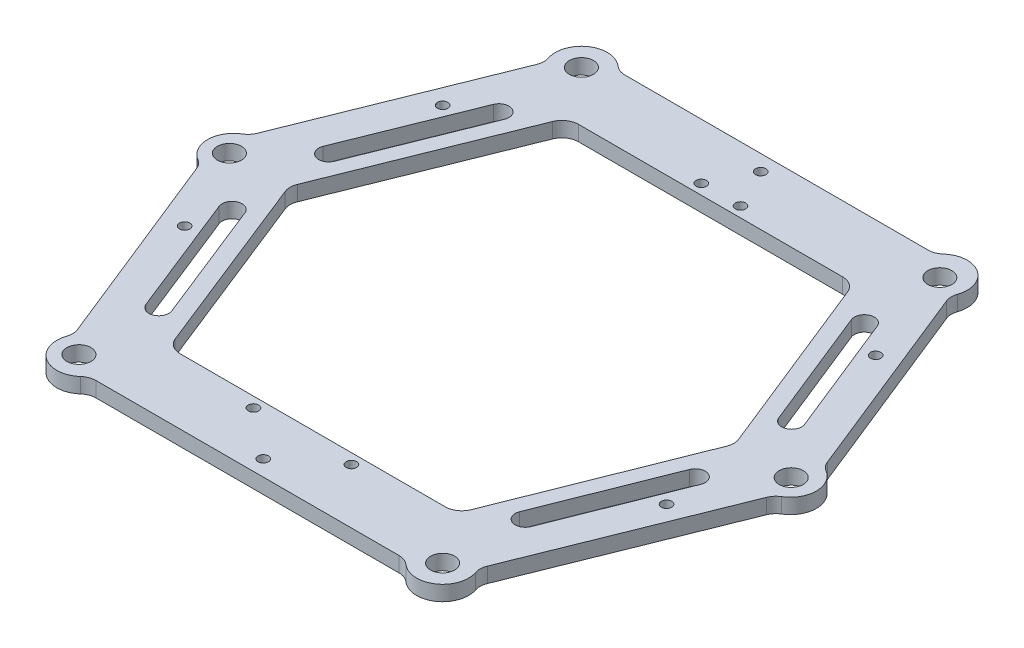
SolidWorks part; units mm, degrees
ref_plane "Front Plane" through (0, 0, 0) normal (0, 0, 1) x (1, 0, 0)
ref_plane "Top Plane" through (0, 0, 0) normal (0, 1, 0) x (1, 0, 0)
ref_plane "Right Plane" through (0, 0, 0) normal (1, 0, 0) x (0, 0, -1)
sketch "Sketch1" plane through (0, 0, 0) normal (0, 1, 0) x (1, 0, 0)
  line L0 (0, 0) -> (0, 80.8355) construction
  line L1 (0, 0) -> (0, -80.8355) construction
  line L2 (0, 0) -> (0, 60.6933) construction
  line L3 (0, 0) -> (0, -60.6933) construction
  line L4 (0, 0) -> (85.09, 0) construction
  line L5 (0, 0) -> (-85.09, 0) construction
  line L6 (0, 0) -> (-54.991, 76.2) construction
  line L7 (0, 0) -> (54.991, -76.2) construction
  line L8 (0, 0) -> (54.991, 76.2) construction
  line L9 (0, 0) -> (-54.991, -76.2) construction
  line L10 (-54.991, 0) -> (-54.991, 76.2) construction
  line L11 (-54.991, 0) -> (-54.991, -76.2) construction
  line L12 (0, 80.8355) -> (58.3363, 80.8355)
  line L13 (0, 80.8355) -> (-58.3363, 80.8355)
  line L14 (58.3363, 80.8355) -> (54.991, 76.2) construction
  line L15 (85.09, 0) -> (90.8065, 0) construction
  line L16 (58.3363, 80.8355) -> (90.8065, 0)
  line L17 (0, 60.6933) -> (43.8003, 60.6933)
  line L19 (54.991, -76.2) -> (58.3363, -80.8355) construction
  line L20 (-54.991, -76.2) -> (-58.3363, -80.8355) construction
  line L21 (-85.09, 0) -> (-90.8065, 0) construction
  line L22 (90.8065, 0) -> (58.3363, -80.8355)
  line L23 (58.3363, -80.8355) -> (-58.3363, -80.8355)
  line L24 (-58.3363, -80.8355) -> (-90.8065, 0)
  line L25 (-90.8065, 0) -> (-58.3363, 80.8355)
  line L26 (0, 60.6933) -> (-43.8003, 60.6933)
  line L29 (-43.947, -60.8965) -> (43.947, -60.8965)
  line L31 (43.8003, 60.6933) -> (68.1798, 0)
  line L32 (68.1798, 0) -> (43.947, -60.8965)
  line L33 (-43.8003, 60.6933) -> (-68.1798, 0)
  line L34 (-68.1798, 0) -> (-43.947, -60.8965)
  circle A0 centre (54.991, 76.2) radius 7.9375
  circle A1 centre (85.09, 0) radius 7.9375
  circle A2 centre (54.991, -76.2) radius 7.9375
  circle A3 centre (-54.991, -76.2) radius 7.9375
  circle A4 centre (-85.09, 0) radius 7.9375
  circle A5 centre (-54.991, 76.2) radius 7.9375
  point P31 (67.7678, 0)
  dimension "D6" = 15.875
  dimension "D1" = 161.671
  dimension "D2" = 20.1422
  dimension "D3" = 152.4
  dimension "D4" = 109.982
  dimension "D5" = 170.18
  dimension "D7" = 19.939
extrude "Boss-Extrude1" add sketch "Sketch1" along normal blind 4.6228 contours L25 L24 L23 L22 L16 L12 L13 L32 L29 L34 L33 L26 L17 L31 | L13 A5 L25 | L25 A5 L13 | L16 A0 L12 | L12 A0 L16 | L22 A1 L16 | L16 A1 L22 | L23 A2 L22 | L22 A2 L23 | L23 A3 L24 | L24 A3 L23 | L24 A4 L25 | L25 A4 L24
hole_wizard "L (0.29) Diameter Hole1" positions "Sketch2" profile "Sketch3" hole size "L" standard "ANSI Inch" end condition through all
sketch "Sketch2" plane through (0, 4.6228, 0) normal (0, 1, 0) x (1, 0, 0)
  point P0 (-54.991, 76.2)
  point P3 (85.6179, -0.2927)
  point P5 (55.3927, 75.3576)
  point P7 (54.991, -76.2)
  point P10 (-55.7883, -76.5703)
  point P12 (-86.0698, -0.2927)
  point P17 (0, 0)
sketch "Sketch3" plane through (-54.991, 4.6228, -76.2) normal (1, 0, 0) x (0, 0, 1)
  line L0 (0, 0) -> (0, 4.6228)
  line L1 (0, 4.6228) -> (3.683, 4.6228)
  line L2 (3.683, 4.6228) -> (3.683, 0)
  line L5 (3.683, 0) -> (0, 0)
  line L11 (0, -6.35) -> (0, 107.95) construction
  dimension "Thru Hole Dia." = 7.366
  dimension "Thru Hole Depth" = 4.6228
sketch "Sketch4" plane through (0, 0, 0) normal (0, 1, 0) x (1, 0, 0)
  line L0 (0, 0.9062) -> (0, -64.0461) construction
  line L1 (0, -64.0461) -> (14.9733, -64.0461) construction
  line L2 (0, -64.0461) -> (-14.9733, -64.0461) construction
  line L3 (0, 0.9062) -> (0, 63.8429) construction
  line L4 (0, 63.8429) -> (5.988, 63.8429) construction
  line L5 (0, 63.8429) -> (-5.988, 63.8429) construction
  line L6 (0, 63.8429) -> (0, 60.6933) construction
  line L7 (43.8003, 60.6933) -> (-43.8003, 60.6933) construction
  line L8 (0, -64.0461) -> (0, -60.8965) construction
  line L9 (-43.947, -60.8965) -> (43.947, -60.8965) construction
  line L10 (0, 0.9062) -> (0, 76.0095) construction
  line L11 (0, 0.9062) -> (0, -76.0095) construction
  line L12 (0, 76.0095) -> (0, 80.8355) construction
  line L13 (0, -76.0095) -> (0, -80.8355) construction
  line L14 (-48.5477, 80.8355) -> (48.5477, 80.8355) construction
  line L15 (48.5477, -80.8355) -> (-48.5477, -80.8355) construction
  line L16 (0, 44.9702) -> (66.1733, 44.9702) construction
  line L17 (0, 44.9702) -> (-66.1733, 44.9702) construction
  line L18 (0, -26.3953) -> (73.6346, -26.3953) construction
  line L19 (0, -26.3953) -> (-73.6346, -26.3953) construction
  line L20 (-66.1733, 44.9702) -> (-71.8301, 47.2424) construction
  line L21 (-87.8114, 7.4564) -> (-61.822, 72.1576) construction
  line L22 (-73.6346, -26.3953) -> (-79.2913, -28.6675) construction
  line L23 (-61.822, -72.1576) -> (-87.8114, -7.4564) construction
  point P33 (66.1733, -40.5517)
  point P35 (64.6197, -39.8714)
  point P36 (0, 0)
  point P37 (68.0505, -40.297)
  dimension "D1" = 29.9466
  dimension "D2" = 11.9761
  dimension "D3" = 127.889
  dimension "D4" = 152.019
  dimension "D5" = 132.3467
  dimension "D6" = 6.096
  dimension "D7" = 147.2692
hole_wizard "1/8 (0.125) Diameter Hole1" positions "3DSketch3" profile "Sketch6" hole size "1/8" standard "ANSI Inch" end condition through all
sketch3d "3DSketch3"
  point P0 (-73.6346, 0, 26.3953)
  point P3 (-66.1733, 0, -44.9702)
  point P6 (66.1733, 0, -44.9702)
  point P9 (73.6346, 0, 26.3953)
  point P12 (0, 0, 76.0095)
  point P15 (14.9733, 0, 64.0461)
  point P18 (-14.9733, 0, 64.0461)
  point P21 (5.988, 0, -63.8429)
  point P24 (-5.988, 0, -63.8429)
  point P27 (0, 0, -76.0095)
  point P31 (14.9733, 0, 64.0461)
  point P33 (14.9733, 0, 64.0461)
  point P35 (-14.9733, 0, 64.0461)
  point P37 (-14.9733, 0, 64.0461)
  point P39 (73.6346, 0, 26.3953)
  point P45 (0, 0, 76.0095)
  point P48 (0, 0, 76.0095)
  point P50 (-73.6346, 0, 26.3953)
  point P52 (-66.1733, 0, -44.9702)
  point P54 (66.1733, 0, -44.9702)
  point P56 (5.988, 0, -63.8429)
  point P58 (-5.988, 0, -63.8429)
  point P60 (0, 0, -76.0095)
  point P63 (0, 0, -76.0095)
  point P64 (-5.988, 0, -63.8429)
  point P65 (5.988, 0, -63.8429)
  point P66 (66.1733, 0, -44.9702)
  point P67 (-66.1733, 0, -44.9702)
  point P68 (-73.6346, 0, 26.3953)
  point P69 (0, 0, 76.0095)
sketch "Sketch6" plane through (0, 0, -76.0095) normal (1, 0, 0) x (0, 0, -1)
  line L0 (0, 0) -> (0, 4.6228)
  line L1 (0, 4.6228) -> (1.5875, 4.6228)
  line L2 (1.5875, 4.6228) -> (1.5875, 0)
  line L5 (1.5875, 0) -> (0, 0)
  line L11 (0, -6.35) -> (0, 107.95) construction
  dimension "Thru Hole Dia." = 3.175
  dimension "Thru Hole Depth" = 4.6228
sketch "Sketch7" plane through (0, 4.6228, 0) normal (0, 1, 0) x (1, 0, 0)
  line L0 (-56.0634, -30.4482) -> (-63.3794, -33.3595) construction
  line L1 (-68.1798, 0) -> (-43.947, -60.8965) construction
  line L2 (-63.3794, -33.3595) -> (-70.7751, -14.7745) construction
  line L3 (-63.3794, -33.3595) -> (-55.9838, -51.9446) construction
  line L4 (-70.7751, -14.7745) -> (-55.9838, -51.9446) construction
  line L5 (-67.943, -13.6475) -> (-53.1518, -50.8177)
  line L6 (-73.6071, -15.9014) -> (-58.8158, -53.0716)
  line L7 (-70.7751, -14.7745) -> (-71.902, -11.9425) construction
  line L8 (-55.9838, -51.9446) -> (-54.8568, -54.7766) construction
  line L9 (-55.9901, 30.3466) -> (-63.2966, 33.2816) construction
  line L10 (-43.8003, 60.6933) -> (-68.1798, 0) construction
  line L11 (-63.2966, 33.2816) -> (-55.841, 51.8426) construction
  line L12 (-55.841, 51.8426) -> (-54.7049, 54.671) construction
  line L13 (-63.2966, 33.2816) -> (-70.7523, 14.7205) construction
  line L14 (-70.7523, 14.7205) -> (-71.8884, 11.8922) construction
  line L15 (-55.841, 51.8426) -> (-70.7523, 14.7205) construction
  line L16 (-53.0126, 50.7065) -> (-67.924, 13.5844)
  line L17 (-58.6693, 52.9787) -> (-73.5807, 15.8566)
  line L18 (0, 0) -> (0, 76.0095) construction
  line L19 (70.7523, 14.7205) -> (71.8884, 11.8922) construction
  line L20 (63.2966, 33.2816) -> (70.7523, 14.7205) construction
  line L21 (55.841, 51.8426) -> (54.7049, 54.671) construction
  line L22 (63.2966, 33.2816) -> (55.841, 51.8426) construction
  line L23 (55.9901, 30.3466) -> (63.2966, 33.2816) construction
  line L24 (55.9838, -51.9446) -> (54.8568, -54.7766) construction
  line L25 (70.7751, -14.7745) -> (71.902, -11.9425) construction
  line L26 (63.3794, -33.3595) -> (55.9838, -51.9446) construction
  line L27 (63.3794, -33.3595) -> (70.7751, -14.7745) construction
  line L28 (56.0634, -30.4482) -> (63.3794, -33.3595) construction
  line L29 (55.841, 51.8426) -> (70.7523, 14.7205) construction
  line L30 (53.0126, 50.7065) -> (67.924, 13.5844)
  line L31 (58.6693, 52.9787) -> (73.5807, 15.8566)
  line L32 (70.7751, -14.7745) -> (55.9838, -51.9446) construction
  line L33 (67.943, -13.6475) -> (53.1518, -50.8177)
  line L34 (73.6071, -15.9014) -> (58.8158, -53.0716)
  arc A0 (-67.943, -13.6475) -> (-73.6071, -15.9014) centre (-70.7751, -14.7745) ccw
  arc A1 (-58.8158, -53.0716) -> (-53.1518, -50.8177) centre (-55.9838, -51.9446) ccw
  arc A2 (-53.0126, 50.7065) -> (-58.6693, 52.9787) centre (-55.841, 51.8426) ccw
  arc A3 (-73.5807, 15.8566) -> (-67.924, 13.5844) centre (-70.7523, 14.7205) ccw
  arc A4 (53.0126, 50.7065) -> (58.6693, 52.9787) centre (55.841, 51.8426) cw
  arc A5 (73.5807, 15.8566) -> (67.924, 13.5844) centre (70.7523, 14.7205) cw
  arc A6 (67.943, -13.6475) -> (73.6071, -15.9014) centre (70.7751, -14.7745) cw
  arc A7 (58.8158, -53.0716) -> (53.1518, -50.8177) centre (55.9838, -51.9446) cw
  point P6 (-63.3794, -33.3595)
  point P23 (-63.2966, 33.2816)
  point P45 (63.2966, 33.2816)
  point P50 (63.3794, -33.3595)
  dimension "D3" = 46.101
  dimension "D1" = 6.096
  dimension "D2" = 4.826
extrude "Cut-Extrude1" cut sketch "Sketch7" against normal through all
fillet "Fillet1" radius 5.08 18 edges at (-87.8114, 2.3114, 7.4564) (-61.822, 2.3114, 72.1576) (48.5477, 2.3114, 80.8355) (-48.5477, 2.3114, 80.8355) (87.8114, 2.3114, 7.4564) (61.822, 2.3114, 72.1576) (87.8114, 2.3114, -7.4564) (61.822, 2.3114, -72.1576) (-48.5477, 2.3114, -80.8355) (48.5477, 2.3114, -80.8355) (-61.822, 2.3114, -72.1576) (-87.8114, 2.3114, -7.4564) (43.947, 2.3114, 60.8965) (43.8003, 2.3114, -60.6933) (68.1798, 2.3114, 0) (-43.947, 2.3114, 60.8965) (-68.1798, 2.3114, 0) (-43.8003, 2.3114, -60.6933)
